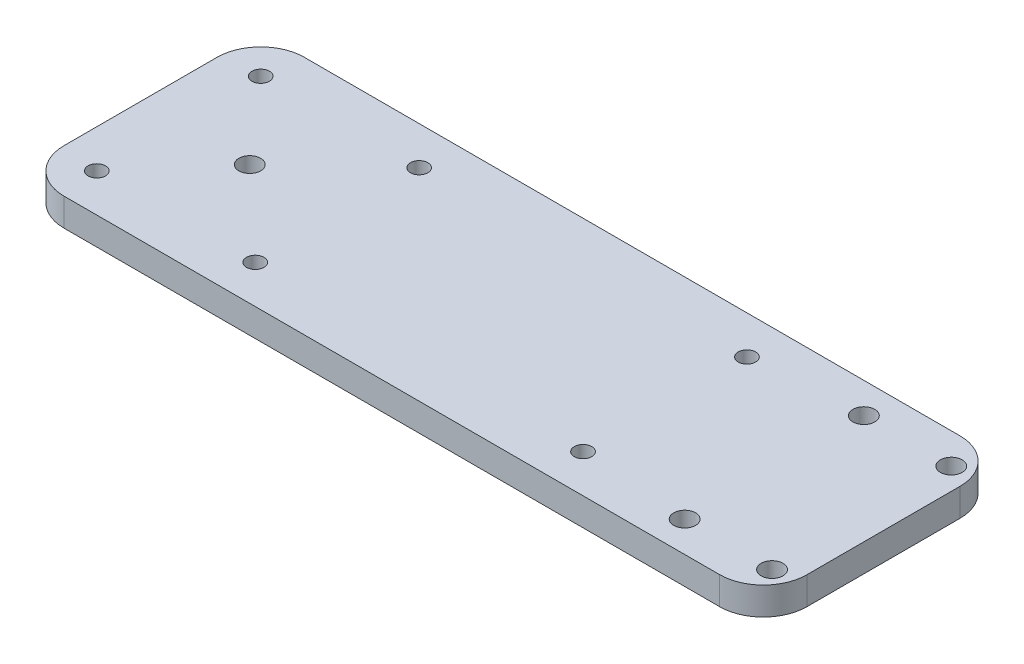
SolidWorks part; units mm, degrees
ref_plane "Front Plane" through (0, 0, 0) normal (0, 0, 1) x (1, 0, 0)
ref_plane "Top Plane" through (0, 0, 0) normal (0, 1, 0) x (1, 0, 0)
ref_plane "Right Plane" through (0, 0, 0) normal (1, 0, 0) x (0, 0, -1)
sketch "Sketch1" plane through (0, 0, 0) normal (0, 1, 0) x (1, 0, 0)
  line L0 (-25, 0) -> (0, 0) construction
  line L1 (-25, 27.5) -> (145, 27.5)
  line L2 (-25, 27.5) -> (-25, -27.5)
  line L3 (-25, -27.5) -> (145, -27.5)
  line L4 (145, 27.5) -> (145, -27.5)
  point P7 (125, 0)
  dimension "D1" = 55
  dimension "D2" = 125
  dimension "D3" = 20
  dimension "D4" = 25
extrude "Boss-Extrude1" add sketch "Sketch1" along normal blind 6.35
fillet "Fillet1" radius 10 4 edges at (-25, 3.175, 27.5) (-25, 3.175, -27.5) (145, 3.175, -27.5) (145, 3.175, 27.5)
hole_wizard "Ø5.0mm Dowel Hole1" positions "Sketch3" profile "Sketch4" hole size "Ø5.0" standard "DIN" end condition up to next
sketch "Sketch3" plane through (0, 6.35, 0) normal (0, 1, 0) x (1, 0, 0)
  point P0 (0, 0)
sketch "Sketch4" plane through (0, 6.35, 0) normal (1, 0, 0) x (0, 0, 1)
  line L0 (0, 0) -> (0, 6.35)
  line L1 (0, 6.35) -> (2.5, 6.35)
  line L2 (2.5, 6.35) -> (2.5, 0)
  line L5 (2.5, 0) -> (0, 0)
  line L11 (0, -6.35) -> (0, 107.95) construction
  dimension "Thru Hole Dia." = 5
  dimension "Thru Hole Depth" = 6.35
hole_wizard "Ø4.0mm Dowel Hole1" positions "Sketch5" profile "Sketch6" hole size "Ø4.0" standard "DIN" end condition up to next
sketch "Sketch5" plane through (0, 6.35, 0) normal (0, 1, 0) x (1, 0, 0)
  line L0 (-25, 17.5) -> (-25, -17.5) construction
  line L1 (-15, -27.5) -> (135, -27.5) construction
  line L2 (20, -18.75) -> (95, -18.75) construction
  line L3 (-25, 0) -> (145, 0) construction
  line L4 (145, -17.5) -> (145, 17.5) construction
  circle A0 centre (0, 0) radius 2.5 construction
  point P0 (-16.25, -18.75)
  point P2 (20, -18.75)
  point P16 (95, -18.75)
  point P17 (170, -18.75)
  point P26 (170, 18.75)
  point P27 (95, 18.75)
  point P28 (20, 18.75)
  point P29 (-16.25, 18.75)
  dimension "D3" = 20
  dimension "D1" = 8.75
  dimension "D2" = 8.75
  dimension "D5" = 75
  dimension "D4" = 3
sketch "Sketch6" plane through (-16.25, 6.35, 18.75) normal (1, 0, 0) x (0, 0, 1)
  line L0 (0, 0) -> (0, 6.35)
  line L1 (0, 6.35) -> (2, 6.35)
  line L2 (2, 6.35) -> (2, 0)
  line L5 (2, 0) -> (0, 0)
  line L11 (0, -6.35) -> (0, 107.95) construction
  dimension "Thru Hole Dia." = 4
  dimension "Thru Hole Depth" = 6.35
hole_wizard "Ø5.0mm Dowel Hole2" positions "Sketch7" profile "Sketch8" hole size "Ø5.0" standard "DIN" end condition through all
sketch "Sketch7" plane through (0, 6.35, 0) normal (0, 1, 0) x (1, 0, 0)
  line L0 (130, 27.5) -> (130, -27.5) construction
  line L1 (135, 27.5) -> (-15, 27.5) construction
  line L2 (-15, -27.5) -> (135, -27.5) construction
  line L4 (145, 0) -> (-25, 0) construction
  line L5 (145, -17.5) -> (145, 17.5) construction
  line L6 (-25, 17.5) -> (-25, -17.5) construction
  point P0 (140, 20.5)
  point P19 (120, 20.5)
  point P20 (140, -20.5)
  point P21 (120, -20.5)
  dimension "D1" = 15
  dimension "D2" = 7
  dimension "D3" = 5
sketch "Sketch8" plane through (140, 6.35, -20.5) normal (1, 0, 0) x (0, 0, 1)
  line L0 (0, 0) -> (0, 6.35)
  line L1 (0, 6.35) -> (2.5, 6.35)
  line L2 (2.5, 6.35) -> (2.5, 0)
  line L5 (2.5, 0) -> (0, 0)
  line L11 (0, -6.35) -> (0, 107.95) construction
  dimension "Thru Hole Dia." = 5
  dimension "Thru Hole Depth" = 6.35
equation "\"Pivot to Pivot Distance\" = 125mm"
equation "\"D2@Sketch1\"=\"Pivot to Pivot Distance\""
equation "\"Plate Thickness\"= 0.25in"
equation "\"D1@Boss-Extrude1\"=\"Plate Thickness\""
